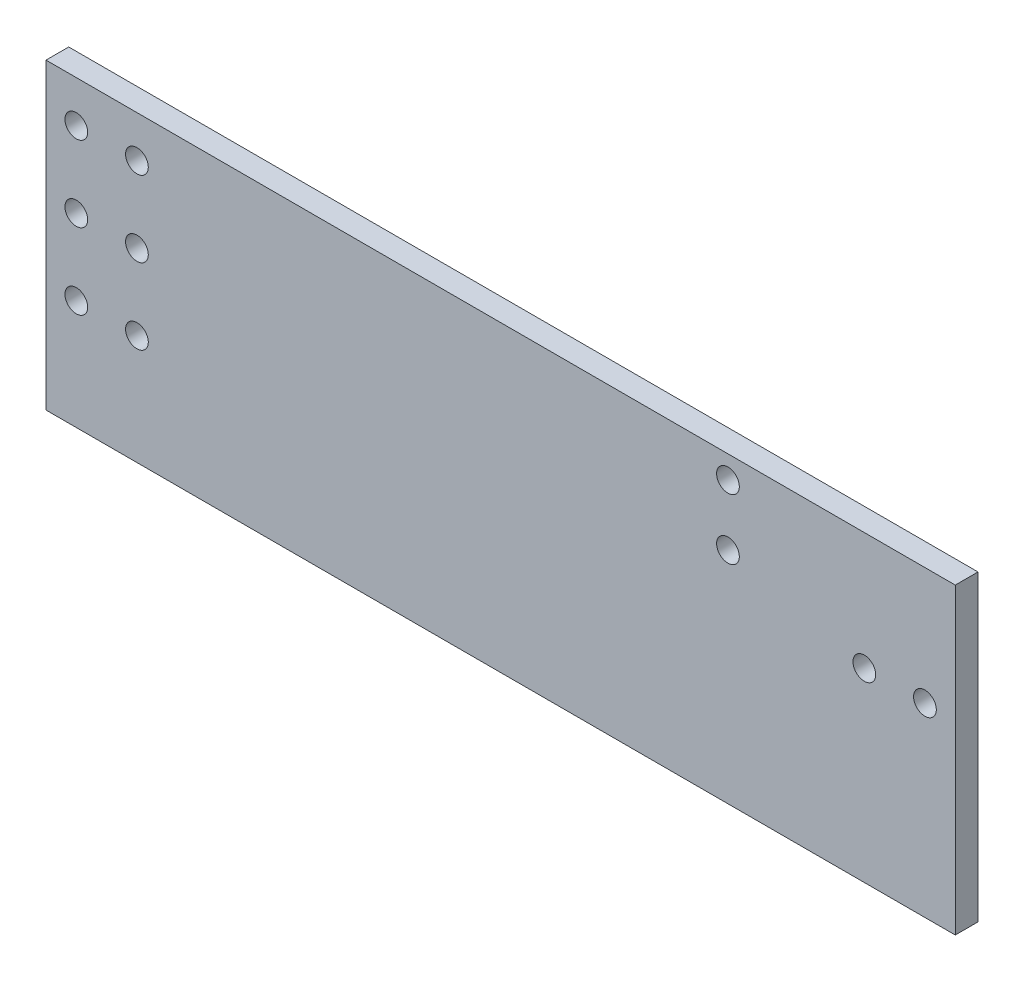
SolidWorks part; units mm, degrees
ref_plane "Front Plane" through (0, 0, 0) normal (0, 0, 1) x (1, 0, 0)
ref_plane "Top Plane" through (0, 0, 0) normal (0, 1, 0) x (1, 0, 0)
ref_plane "Right Plane" through (0, 0, 0) normal (1, 0, 0) x (0, 0, -1)
sketch "Sketch1" plane through (0, 0, 0) normal (0, 0, 1) x (1, 0, 0)
  line L0 (60, 0) -> (-49940, 0) construction
  line L1 (-60, -27.5) -> (60, -27.5)
  line L2 (-60, -27.5) -> (-60, 27.5)
  line L3 (-60, 27.5) -> (60, 27.5)
  line L4 (60, -27.5) -> (60, 27.5)
  line L5 (-60, -27.5) -> (60, 27.5) construction
  line L6 (-60, 27.5) -> (60, -27.5) construction
  circle A0 centre (30, 4.5) radius 1.5
  circle A1 centre (30, 12.5) radius 1.5
  circle A2 centre (56, 0) radius 1.5
  circle A3 centre (48, 0) radius 1.5
  circle A4 centre (-56, 10) radius 1.5
  circle A5 centre (-48, 10) radius 1.5
  circle A6 centre (-56, -10) radius 1.5
  circle A7 centre (-48, -10) radius 1.5
  circle A8 centre (-56, 0) radius 1.5
  circle A9 centre (-48, 0) radius 1.5
  point P0 (0, 0)
  point P12 (60, 0)
  dimension "D6" = 3
  dimension "D7" = 3
  dimension "D11" = 3
  dimension "D12" = 3
  dimension "D15" = 3
  dimension "D16" = 3
  dimension "D19" = 3
  dimension "D20" = 3
  dimension "D1" = 120
  dimension "D2" = 55
  dimension "D3" = 15
  dimension "D4" = 30
  dimension "D5" = 8
  dimension "D8" = 30
  dimension "D9" = 4
  dimension "D10" = 8
  dimension "D13" = 4
  dimension "D14" = 8
  dimension "D17" = 10
  dimension "D18" = 10
  dimension "D21" = 8
  dimension "D22" = 4
extrude "Boss-Extrude1" add sketch "Sketch1" along normal blind 3
sketch "Sketch2" plane through (0, 0, 3) normal (0, 0, 1) x (1, 0, 0)
  line L0 (-60, 15.5) -> (60, 15.5)
  line L1 (60, -27.5) -> (60, 27.5) construction
  line L2 (-60, 27.5) -> (-60, -27.5) construction
  line L3 (-60, 27.5141) -> (-60, 27.5)
  line L4 (-60, 27.5) -> (-60, 15.5)
  line L5 (60, 27.5) -> (60, 15.5)
  line L6 (60, 27.5) -> (-60, 27.5141)
  circle A0 centre (30, 12.5) radius 1.5 construction
  dimension "D1" = 3
  dimension "D2" = 120
  dimension "D3" = 179.993
extrude "Cut-Extrude1" cut sketch "Sketch2" against normal through all
sketch "Sketch3" plane through (0, 0, 3) normal (0, 0, 1) x (1, 0, 0)
  line L0 (60, -27.5) -> (60, 15.5) construction
  line L1 (-60, -27.5) -> (60, -27.5)
  line L2 (-60, -27.5) -> (-60, -24.5)
  line L3 (-60, -24.5) -> (60, -24.5)
  line L4 (60, -27.5) -> (60, -24.5)
  dimension "D1" = 3
extrude "Cut-Extrude2" cut sketch "Sketch3" against normal through all
